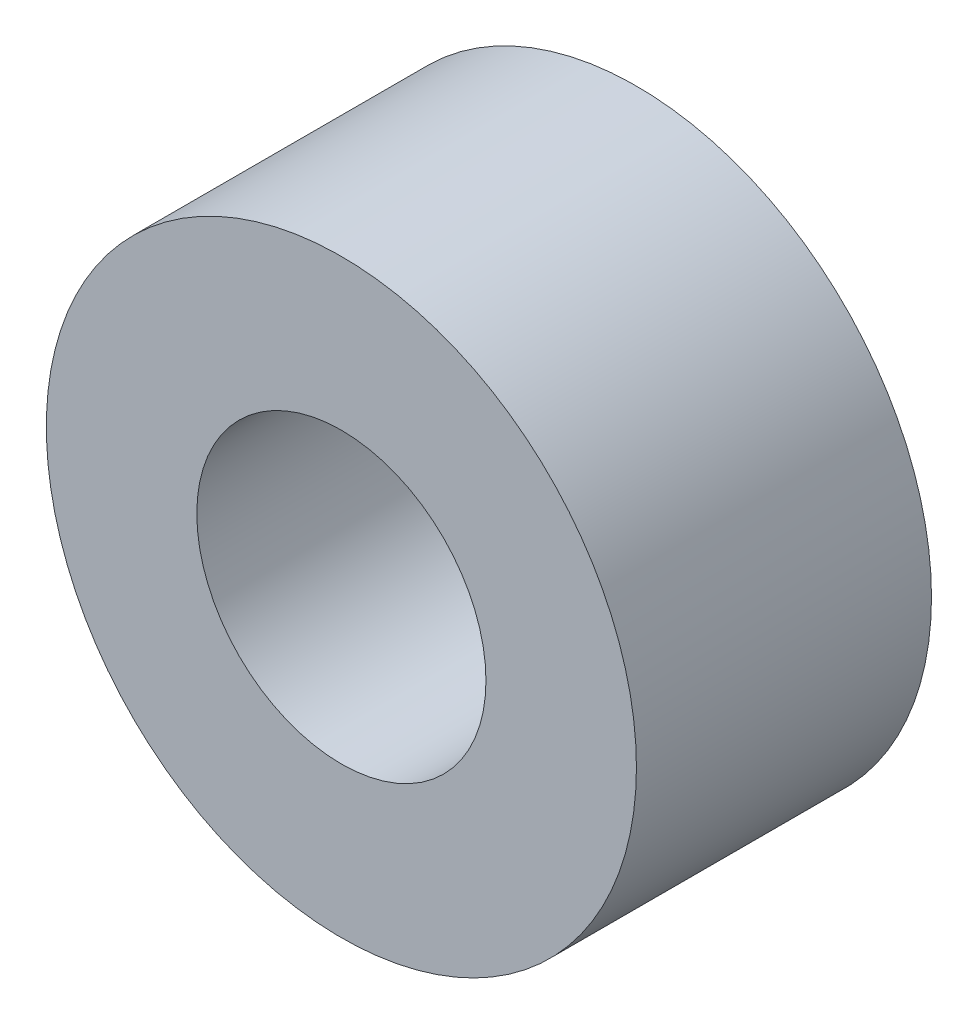
SolidWorks part; units mm, degrees
ref_plane "前视基准面" through (0, 0, 0) normal (0, 0, 1) x (1, 0, 0)
ref_plane "上视基准面" through (0, 0, 0) normal (0, 1, 0) x (1, 0, 0)
ref_plane "右视基准面" through (0, 0, 0) normal (1, 0, 0) x (0, 0, -1)
sketch "草图1" plane through (0, 0, 0) normal (0, 0, 1) x (1, 0, 0)
  circle A0 centre (0, 0) radius 5
  circle A1 centre (0, 0) radius 2.45
  dimension "D1" = 10
  dimension "D2" = 4.9
extrude "凸台-拉伸1" add sketch "草图1" along normal blind 5
